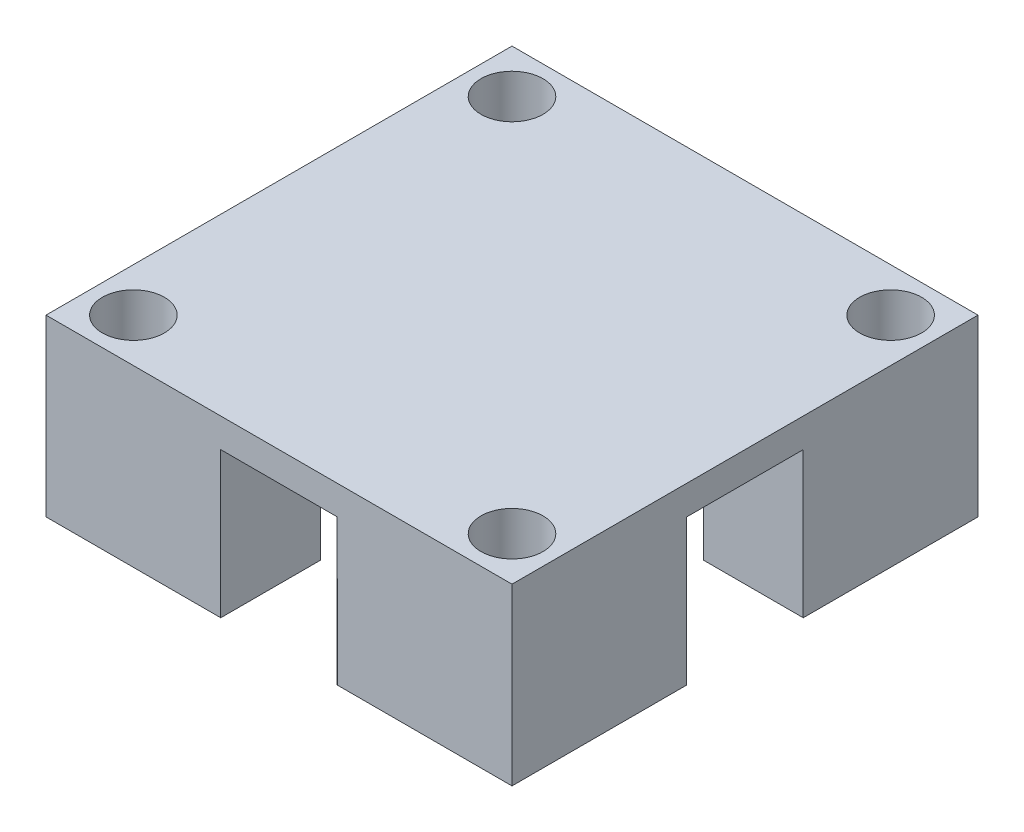
SolidWorks part; units mm, degrees
material "Copper"
ref_plane "Front Plane" through (0, 0, 0) normal (0, 0, 1) x (1, 0, 0)
ref_plane "Top Plane" through (0, 0, 0) normal (0, 1, 0) x (1, 0, 0)
ref_plane "Right Plane" through (0, 0, 0) normal (1, 0, 0) x (0, 0, -1)
sketch "Sketch1" plane through (0, 0, 0) normal (0, 1, 0) x (1, 0, 0)
  line L1 (-25.4, 25.4) -> (25.4, 25.4)
  line L2 (-25.4, 25.4) -> (-25.4, -25.4)
  line L3 (-25.4, -25.4) -> (25.4, -25.4)
  line L4 (25.4, 25.4) -> (25.4, -25.4)
  line L5 (-25.4, 25.4) -> (25.4, -25.4) construction
  line L6 (-25.4, -25.4) -> (25.4, 25.4) construction
  point P0 (0, 0)
  dimension "D1" = 50.8
  dimension "D2" = 50.8
extrude "Boss-Extrude1" add sketch "Sketch1" along normal blind 19.05
hole_wizard "1/4 Clearance Hole1" positions "Sketch8" profile "Sketch7" hole size "1/4" standard "ANSI Inch" end condition through all
sketch "Sketch8" plane through (0, 19.05, 0) normal (0, 1, 0) x (1, 0, 0)
  point P0 (-20.6375, 20.6375)
  point P2 (20.6375, 20.6375)
  point P4 (20.6375, -20.6375)
  point P6 (-20.6375, -20.6375)
sketch "Sketch7" plane through (-20.6375, 19.05, -20.6375) normal (1, 0, 0) x (0, 0, 1)
  line L0 (0, 0) -> (0, 19.05)
  line L1 (0, 19.05) -> (3.3782, 19.05)
  line L2 (3.3782, 19.05) -> (3.3782, 0)
  line L5 (3.3782, 0) -> (0, 0)
  line L11 (0, -6.35) -> (0, 107.95) construction
  dimension "Thru Hole Dia." = 6.7564
  dimension "Thru Hole Depth" = 19.05
sketch "Sketch9" plane through (0, 0, 0) normal (0, -1, 0) x (1, 0, 0)
  line L0 (-25.4, -25.4) -> (-25.4, 25.4) construction
  line L1 (-25.4, 6.35) -> (25.4, 6.35)
  line L2 (-25.4, 6.35) -> (-25.4, -6.35)
  line L3 (-25.4, -6.35) -> (25.4, -6.35)
  line L4 (25.4, 6.35) -> (25.4, -6.35)
  line L5 (25.4, 25.4) -> (25.4, -25.4) construction
  line L6 (-25.4, 25.4) -> (25.4, 25.4) construction
  line L7 (-6.35, 25.4) -> (6.35, 25.4)
  line L8 (-6.35, 25.4) -> (-6.35, -25.4)
  line L9 (-6.35, -25.4) -> (6.35, -25.4)
  line L10 (6.35, 25.4) -> (6.35, -25.4)
  line L11 (25.4, -25.4) -> (-25.4, -25.4) construction
  circle A0 centre (0, 0) radius 15.875
  line M5 (25.4, -25.4) -> (25.4, 25.4)
  line M6 (25.4, 25.4) -> (-25.4, 25.4)
  line M7 (-25.4, 25.4) -> (-25.4, -25.4)
  line M8 (-25.4, -25.4) -> (25.4, -25.4)
  dimension "D1" = 12.7
  dimension "D3" = 31.75
  dimension "D2" = 12.7
  dimension "D4" = 6.35
  dimension "D5" = 6.35
extrude "Cut-Extrude1" cut sketch "Sketch9" against normal blind 15.875 contours L8 A0 L1 | A0 L10 L8 M6 | L1 A0 L10 | A0 L3 L1 M5 | L10 A0 L3 | A0 L8 L10 M8 | L3 A0 L8 | A0 L1 L3 M7 | L1 A0 L3 L8 | L8 A0 L10 L3 | L3 A0 L1 L10 | L10 L1 L8 L3 | L10 A0 L8 L1
